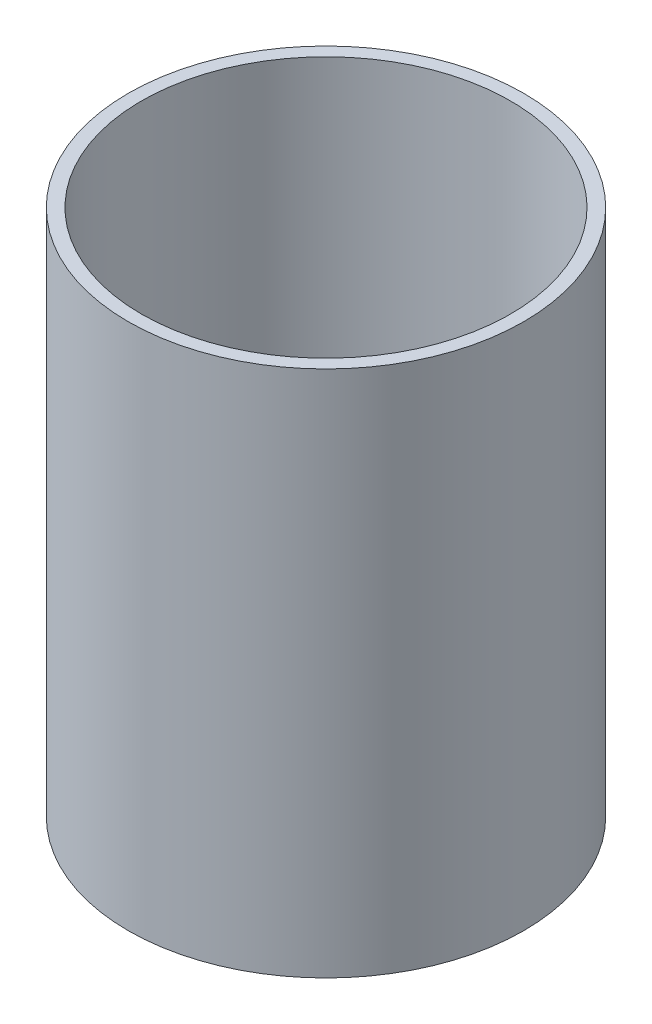
SolidWorks part; units mm, degrees
ref_plane "Plano frontal" through (0, 0, 0) normal (0, 0, 1) x (1, 0, 0)
ref_plane "Plano superior" through (0, 0, 0) normal (0, 1, 0) x (1, 0, 0)
ref_plane "Plano direito" through (0, 0, 0) normal (1, 0, 0) x (0, 0, -1)
sketch "Esboço1" plane through (0, 0, 0) normal (0, 1, 0) x (1, 0, 0)
  circle A0 centre (0, 0) radius 15
  circle A1 centre (0, 0) radius 14
  dimension "D1" = 30
  dimension "D2" = 1
sketch "Esboço2" plane through (0, 0, 0) normal (0, 0, 1) x (1, 0, 0)
  line L0 (0, 0) -> (0, -40)
  dimension "D1" = 40
sweep "Varredura1" add profiles "Esboço1" path "Esboço2"
